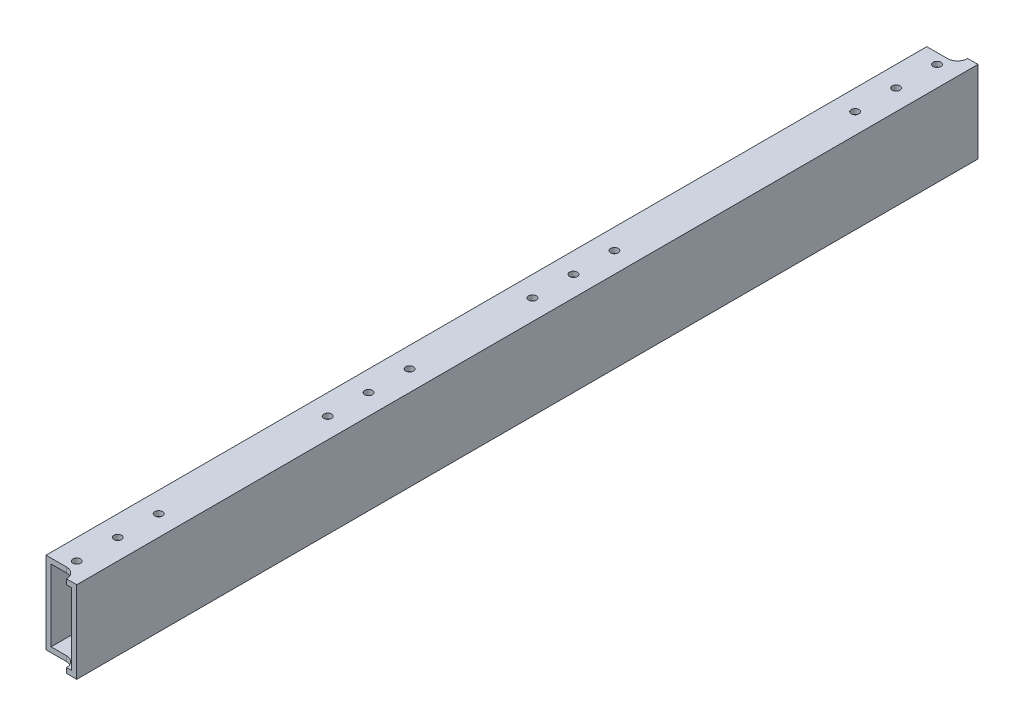
SolidWorks part; units mm, degrees
ref_plane "Front Plane" through (0, 0, 0) normal (0, 0, 1) x (1, 0, 0)
ref_plane "Top Plane" through (0, 0, 0) normal (0, 1, 0) x (1, 0, 0)
ref_plane "Right Plane" through (0, 0, 0) normal (1, 0, 0) x (0, 0, -1)
sketch "Sketch1" plane through (0, 0, 0) normal (0, 0, 1) x (1, 0, 0)
  line L1 (-12.7, 25.4) -> (12.7, 25.4)
  line L2 (-12.7, 25.4) -> (-12.7, -25.4)
  line L3 (-12.7, -25.4) -> (12.7, -25.4)
  line L4 (12.7, 25.4) -> (12.7, -25.4)
  line L5 (0, -25.4) -> (0, 25.4) construction
  line L6 (-12.7, 0) -> (12.7, 0) construction
  point P0 (0, 0)
  dimension "D1" = 25.4
  dimension "D2" = 50.8
extrude "Boss-Extrude1" add sketch "Sketch1" along normal mid plane 558.8
shell "Shell1" thickness 3.175
sketch "Sketch3" plane through (0, 25.4, 0) normal (0, 1, 0) x (1, 0, 0)
  line L1 (0, 66.675) -> (0, 15.875) construction
  line L3 (6.35, 279.4) -> (-12.7, 279.4)
  line L4 (-12.7, 279.4) -> (-12.7, 273.05)
  line L5 (-12.7, -279.4) -> (-12.7, 279.4) construction
  line L6 (-12.7, 273.05) -> (0, 273.05)
  line L7 (0, 0) -> (77.7351, 0) construction
  line L8 (-12.7, -273.05) -> (0, -273.05)
  line L9 (-12.7, -279.4) -> (-12.7, -273.05)
  line L10 (6.35, -279.4) -> (-12.7, -279.4)
  line L11 (12.7, -279.4) -> (-12.7, -279.4) construction
  line L12 (0, -111.125) -> (0, -60.325) construction
  circle A0 centre (0, 279.4) radius 4.7625 construction
  circle A1 centre (0, 266.7) radius 2.3813
  circle A2 centre (0, 241.3) radius 2.3813
  arc A3 (6.35, 279.4) -> (0, 273.05) centre (0, 279.4) cw
  circle A4 centre (0, 215.9) radius 2.3813
  circle A5 centre (0, -279.4) radius 4.7625 construction
  circle A6 centre (0, -215.9) radius 2.3812
  arc A7 (6.35, -279.4) -> (0, -273.05) centre (0, -279.4) ccw
  circle A8 centre (0, -241.3) radius 2.3812
  circle A9 centre (0, -266.7) radius 2.3813
  circle A16 centre (0, 66.675) radius 2.3812
  circle A17 centre (0, 15.875) radius 2.3812
  circle A18 centre (0, 41.275) radius 2.3812
  circle A19 centre (0, -85.725) radius 2.3812
  circle A20 centre (0, -60.325) radius 2.3812
  circle A21 centre (0, -111.125) radius 2.3812
  point P33 (0, -85.725)
  point P47 (0, 41.275)
  point P54 (0, 41.275)
  dimension "D1" = 9.525
  dimension "D2" = 4.7625
  dimension "D4" = 25.4
  dimension "D5" = 6.35
  dimension "D6" = 25.4
  dimension "D7" = 25.4
  dimension "D8" = 225.425
  dimension "D9" = 25.4
  dimension "D3" = 12.7
  dimension "D10" = 127
extrude "Cut-Extrude1" cut sketch "Sketch3" against normal through all
